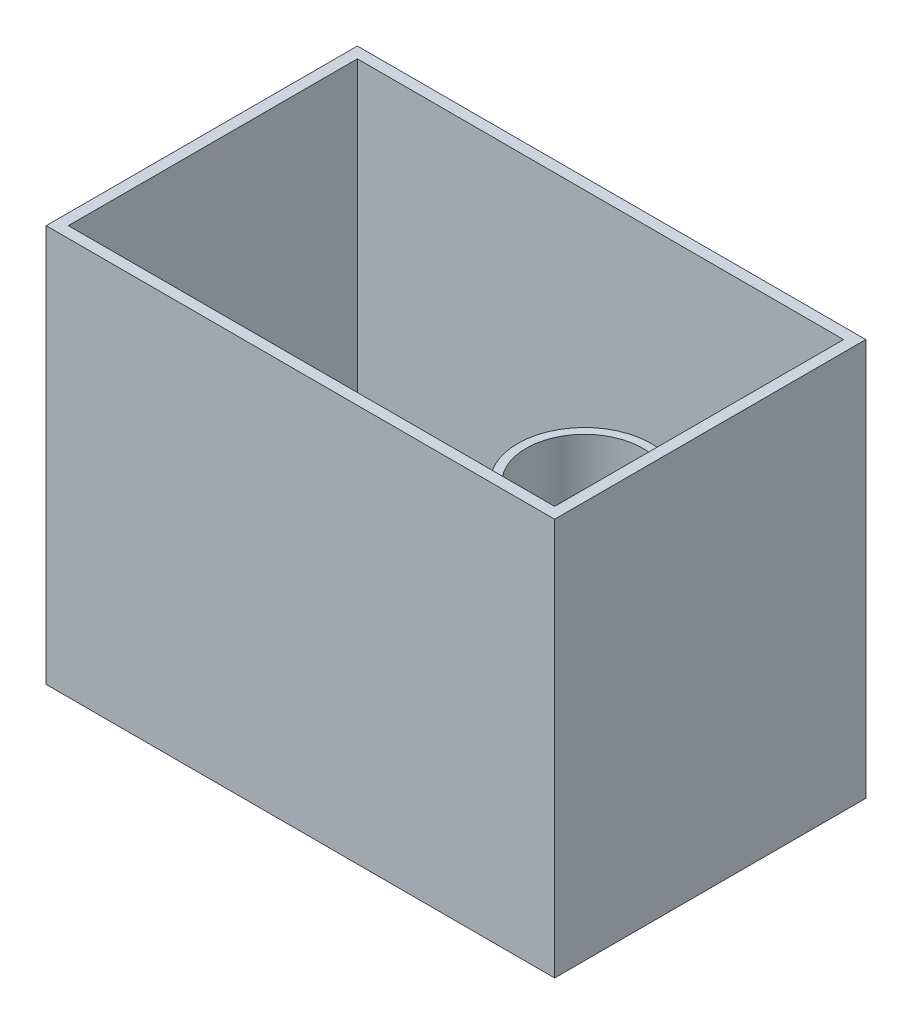
SolidWorks part; units mm, degrees
ref_plane "Front" through (0, 0, 0) normal (0, 0, 1) x (1, 0, 0)
ref_plane "Top" through (0, 0, 0) normal (0, 1, 0) x (1, 0, 0)
ref_plane "Right" through (0, 0, 0) normal (1, 0, 0) x (0, 0, -1)
sketch "Sketch1" plane through (0, 0, 0) normal (0, 1, 0) x (1, 0, 0)
  line L1 (0, 0) -> (183, 0)
  line L2 (0, 0) -> (0, -112)
  line L3 (0, -112) -> (183, -112)
  line L4 (183, 0) -> (183, -112)
  dimension "D1" = 112
  dimension "D2" = 183
extrude "Boss-Extrude1" add sketch "Sketch1" along normal blind 4
sketch "Sketch2" plane through (0, 4, 0) normal (0, 1, 0) x (1, 0, 0)
  line L0 (4, -4) -> (4, -108)
  line L1 (0, 0) -> (183, 0)
  line L2 (0, 0) -> (0, -112)
  line L3 (0, -112) -> (183, -112)
  line L4 (183, 0) -> (183, -112)
  line L5 (4, -108) -> (179, -108)
  line L6 (179, -4) -> (179, -108)
  line L7 (4, -4) -> (179, -4)
  dimension "D1" = 4
extrude "Boss-Extrude2" add sketch "Sketch2" along normal blind 139
sketch "Sketch3" plane through (0, 0, 0) normal (0, -1, 0) x (-1, 0, 0)
  line L0 (0, 0) -> (0, -112) construction
  circle A0 centre (-61, -56) radius 35.5
  dimension "D1" = 71
  dimension "D2" = 61
extrude "Cut-Extrude1" cut sketch "Sketch3" against normal blind 4
sketch "Sketch4" plane through (0, 0, 0) normal (0, -1, 0) x (-1, 0, 0)
  circle A0 centre (-61, -56) radius 39.25
  dimension "D1" = 78.5
extrude "Cut-Extrude2" cut sketch "Sketch4" against normal blind 2
sketch "Sketch5" plane through (0, 4, 0) normal (0, 1, 0) x (1, 0, 0)
  line L0 (179, -108) -> (179, -4) construction
  circle A0 centre (137.75, -56) radius 21
  dimension "D1" = 42
  dimension "D2" = 41.25
extrude "Cut-Extrude3" cut sketch "Sketch5" against normal blind 4
sketch "Sketch6" plane through (0, 4, 0) normal (0, 1, 0) x (1, 0, 0)
  circle A0 centre (137.75, -56) radius 21
  circle A1 centre (137.75, -56) radius 24
  dimension "D2" = 42
  dimension "D1" = 3
extrude "Boss-Extrude3" add sketch "Sketch6" along normal blind 100
equation "\"D1@Sketch1\"=103 + 1+8"
equation "\"D2@Sketch1\"=174 + 1+8"
equation "\"D1@Boss-Extrude2\"=134+1+4"
equation "\"D2@Sketch3\"=\"D2@Sketch1\"/3"
equation "\"D2@Sketch5\"=( \"D2@Sketch1\"/3*2-4-\"D1@Sketch3\"/2)/2"
